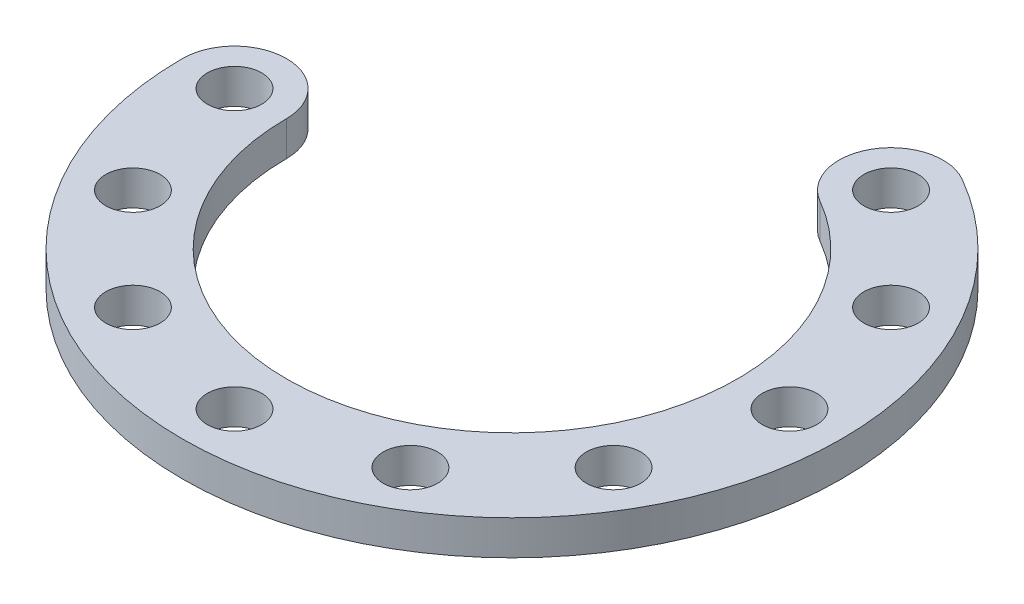
SolidWorks part; units mm, degrees
ref_plane "Front Plane" through (0, 0, 0) normal (0, 0, 1) x (1, 0, 0)
ref_plane "Top Plane" through (0, 0, 0) normal (0, 1, 0) x (1, 0, 0)
ref_plane "Right Plane" through (0, 0, 0) normal (1, 0, 0) x (0, 0, -1)
sketch "Sketch1" plane through (0, 0, 0) normal (0, 1, 0) x (1, 0, 0)
  circle A0 centre (0, 0) radius 25.4 construction
  circle A1 centre (25.4, 0) radius 2.4892
  circle A2 centre (21.997, -12.7) radius 2.4892
  circle A3 centre (12.7, -21.997) radius 2.4892
  circle A4 centre (0, -25.4) radius 2.4892
  circle A5 centre (-12.7, -21.997) radius 2.4892
  circle A6 centre (-21.997, -12.7) radius 2.4892
  circle A7 centre (-25.4, 0) radius 2.4892
  circle A8 centre (-21.997, 12.7) radius 2.4892 [skipped]
  circle A9 centre (-12.7, 21.997) radius 2.4892 [skipped]
  circle A10 centre (0, 25.4) radius 2.4892 [skipped]
  circle A11 centre (12.7, 21.997) radius 2.4892
  circle A12 centre (21.997, 12.7) radius 2.4892
  arc A13 (-25.4, 0) -> (12.7, 21.997) centre (0, 0) ccw construction
  arc A14 (-30.1625, 0) -> (15.0812, 26.1215) centre (0, 0) ccw
  arc A15 (-20.6375, 0) -> (10.3187, 17.8726) centre (0, 0) ccw
  arc A16 (-20.6375, 0) -> (-30.1625, 0) centre (-25.4, 0) ccw
  arc A17 (15.0812, 26.1215) -> (10.3187, 17.8726) centre (12.7, 21.997) ccw
  point P6 (12.7, -21.997)
  point P30 (0, 0)
  point P34 (12.7464, 21.9702)
  point P35 (0, 0)
  point P36 (12.7, 21.997)
  point P37 (21.997, 12.7)
  dimension "D1" = 50.8
  dimension "D2" = 4.9784
  dimension "D4" = 9.525
  dimension "D3" = 12
extrude "Boss-Extrude1" add sketch "Sketch1" along normal blind 3.175
